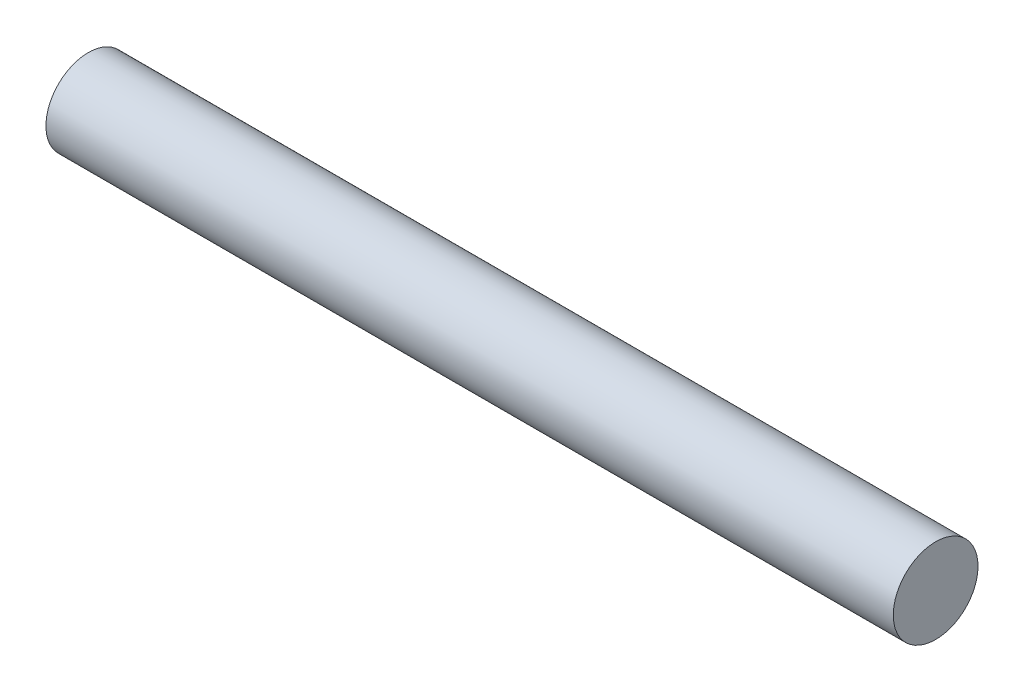
SolidWorks part; units mm, degrees
ref_plane "Front Plane" through (0, 0, 0) normal (0, 0, 1) x (1, 0, 0)
ref_plane "Top Plane" through (0, 0, 0) normal (0, 1, 0) x (1, 0, 0)
ref_plane "Right Plane" through (0, 0, 0) normal (1, 0, 0) x (0, 0, -1)
sketch "Sketch1" plane through (0, 0, 0) normal (1, 0, 0) x (0, 0, -1)
  circle A0 centre (0, 0) radius 1.5
  dimension "D1" = 3
extrude "Boss-Extrude1" add sketch "Sketch1" along normal blind 30
